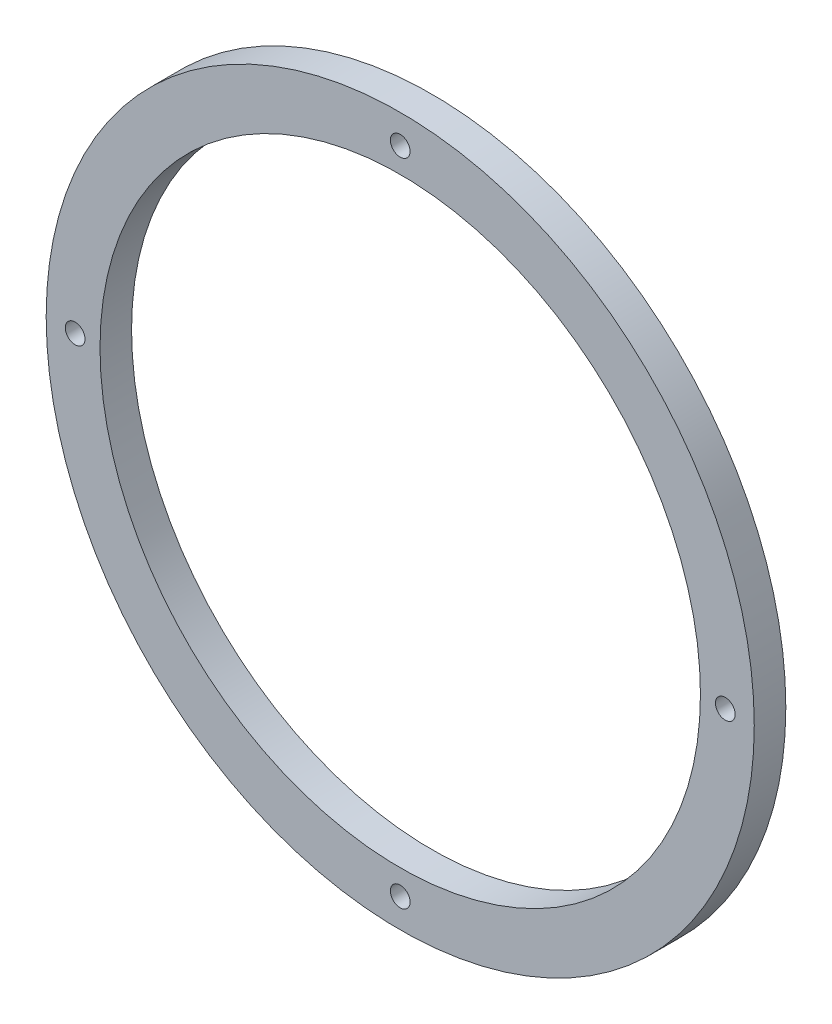
SolidWorks part; units mm, degrees
material "6061 Alloy"
ref_plane "Front Plane" through (0, 0, 0) normal (0, 0, 1) x (1, 0, 0)
ref_plane "Top Plane" through (0, 0, 0) normal (0, 1, 0) x (1, 0, 0)
ref_plane "Right Plane" through (0, 0, 0) normal (1, 0, 0) x (0, 0, -1)
sketch "Sketch1" plane through (0, 0, 0) normal (0, 0, 1) x (1, 0, 0)
  line L0 (0, 78.5) -> (0, 0) construction
  line L1 (0, 0) -> (-78.5, 0) construction
  circle A0 centre (0, 0) radius 72.5
  circle A1 centre (0, 0) radius 85.5
  circle A2 centre (0, 78.5) radius 2.3812
  circle A3 centre (78.5, 0) radius 2.3813
  circle A4 centre (0, -78.5) radius 2.3812
  circle A5 centre (-78.5, 0) radius 2.3813
  point P16 (0, 0)
  dimension "D1" = 145
  dimension "D4" = 4.7625
  dimension "D3" = 78.5
  dimension "D6" = 78.5
  dimension "D2" = 13
  dimension "D5" = 4
extrude "Boss-Extrude1" add sketch "Sketch1" along normal blind 7.62
